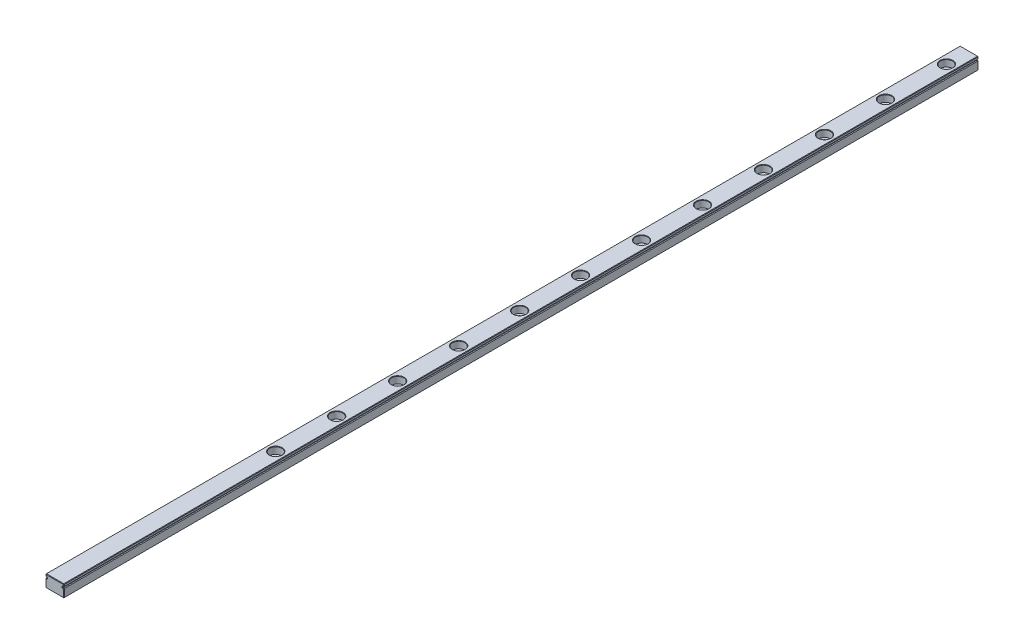
SolidWorks part; units mm, degrees
material "AISI 304"
ref_plane "Front Plane" through (0, 0, 0) normal (0, 0, 1) x (1, 0, 0)
ref_plane "Top Plane" through (0, 0, 0) normal (0, 1, 0) x (1, 0, 0)
ref_plane "Right Plane" through (0, 0, 0) normal (1, 0, 0) x (0, 0, -1)
sketch "Sketch1" plane through (0, 0, 0) normal (0, 0, 1) x (1, 0, 0)
  line L0 (0, 0) -> (0, 8) construction
  line L1 (0, 8) -> (12, 8)
  line L2 (0, 0) -> (12, 0)
  line L3 (0, 8) -> (0, 6.75)
  line L4 (0, 6.75) -> (0.5, 6.25) construction
  line L5 (0.5, 6.25) -> (1, 6.25)
  line L6 (0.5, 5.75) -> (0, 5.25) construction
  line L7 (0, 5.25) -> (0, 0)
  line L8 (1, 6.25) -> (1, 5.75)
  line L9 (1, 5.75) -> (0.5, 5.75)
  line L10 (0.5, 5.75) -> (0.75, 6) construction
  line L11 (0.75, 6) -> (0.5, 6.25) construction
  line L12 (0, 6.75) -> (0, 6.559)
  line L13 (0, 5.25) -> (0, 5.441)
  line L14 (6, 8) -> (6, 0) construction
  line L15 (11.25, 6) -> (11.5, 6.25) construction
  line L16 (11.5, 5.75) -> (11.25, 6) construction
  line L17 (11.5, 5.75) -> (12, 5.25) construction
  line L18 (12, 6.75) -> (11.5, 6.25) construction
  line L19 (12, 0) -> (12, 8) construction
  line L20 (12, 5.25) -> (12, 5.441)
  line L21 (12, 6.75) -> (12, 6.559)
  line L22 (11, 5.75) -> (11.5, 5.75)
  line L23 (11, 6.25) -> (11, 5.75)
  line L24 (12, 5.25) -> (12, 0)
  line L25 (11.5, 6.25) -> (11, 6.25)
  line L26 (12, 8) -> (12, 6.75)
  arc A0 (0, 5.441) -> (0.5, 5.75) centre (0, 6) ccw
  arc A1 (0.5, 6.25) -> (0, 6.559) centre (0, 6) ccw
  arc A2 (11.5, 6.25) -> (12, 6.559) centre (12, 6) cw
  arc A3 (12, 5.441) -> (11.5, 5.75) centre (12, 6) cw
  point P4 (1, 6)
  point P28 (11, 6)
  dimension "D1" = 8
  dimension "D2" = 6
  dimension "D3" = 0.5
  dimension "D4" = 45
  dimension "D5" = 2
  dimension "D6" = 1
extrude "Boss-Extrude1" add sketch "Sketch1" along normal blind 600
chamfer "Chamfer1" distance 0.3 angle 45 36 edges at (0, 0, 300) (12, 0, 300) (0, 8, 300) (12, 8, 300) (0.2939, 5.5245, 600) (0.75, 5.75, 600) (1, 6, 600) (0.75, 6.25, 600) (0.2939, 6.4755, 600) (0, 7.2795, 600) (6, 8, 600) (12, 7.2795, 600) (11.7061, 6.4755, 600) (11.25, 6.25, 600) (11, 6, 600) (11.25, 5.75, 600) (11.7061, 5.5245, 600) (12, 2.7205, 600) (6, 0, 600) (0, 2.7205, 600) (12, 2.7205, 0) (11.7061, 5.5245, 0) (11.25, 5.75, 0) (11, 6, 0) (11.25, 6.25, 0) (11.7061, 6.4755, 0) (12, 7.2795, 0) (6, 0, 0) (0, 2.7205, 0) (0.2939, 5.5245, 0) (0.75, 5.75, 0) (1, 6, 0) (0.75, 6.25, 0) (0.2939, 6.4755, 0) (0, 7.2795, 0) (6, 8, 0)
hole_wizard "CBORE for M5 Hex Head Bolt1" positions "3DSketch1" profile "Sketch3" counterbore size "M5" standard "ANSI Metric" end condition through all
sketch3d "3DSketch1"
  line L0 (6, 8, 0) -> (6, 8, 15) construction
  line L1 (11.7, 8, 0) -> (0.3, 8, 0) construction
  point P0 (6, 8, 15)
  dimension "D1" = 15
sketch "Sketch3" plane through (6, 8, 15) normal (1, 0, 0) x (0, 0, 1)
  line L0 (0, 0) -> (0, 8)
  line L1 (2.25, 7.75) -> (2.5, 8)
  line L2 (4, 4.5) -> (2.25, 4.5)
  line L3 (2.25, 4.5) -> (2.25, 7.75)
  line L5 (4, 4.5) -> (4, 0.25)
  line L6 (4, 0.25) -> (4.25, 0)
  line L7 (4.25, 0) -> (0, 0)
  line L8 (-4, 0.25) -> (-4.25, 0) construction
  line L11 (0, -6.35) -> (0, 107.95) construction
  line L12 (2.5, 8) -> (0, 8)
  line L13 (-2.25, 7.75) -> (-2.5, 8) construction
  dimension "Thru Hole Dia." = 4.5
  dimension "Thru Hole Depth" = 8
  dimension "C'Bore Dia." = 8
  dimension "C'Bore Depth" = 4.5
  dimension "Near C'Sink Dia." = 8.5
  dimension "Near C'Sink Angle" = 90
  dimension "Far C'Sink Dia." = 5
  dimension "Far C'Sink Angle" = 90
pattern_linear "LPattern1" count 12 spacing 40 along (0, 0, 1) of "CBORE for M5 Hex Head Bolt1"
sketch "Sketch4" plane through (0, 0, 600) normal (0, 0, 1) x (1, 0, 0)
  line L0 (6, 0.3) -> (6, 10.6503) construction
  line L1 (0.3, 0.3) -> (11.7, 0.3) construction
sketch "Sketch6" plane through (0, 0, 0) normal (0, 0, -1) x (-1, 0, 0)
  line L0 (-6, 0.3) -> (-6, 11.2574) construction
  line L1 (-11.7, 0.3) -> (-0.3, 0.3) construction
  line L2 (-6, 7.7) -> (-6, -3.7799) construction
  line L3 (-0.3, 7.7) -> (-11.7, 7.7) construction
sketch "Sketch8" plane through (0, 0, 0) normal (0, -1, 0) x (1, 0, 0)
  line L0 (6, -999.7) -> (6, 49000.3) construction
  line L1 (0.3, 0.3) -> (11.7, 0.3) construction
  point P5 (6, 0.3)
sketch "Sketch10" plane through (0, 0, 0) normal (0, 0, -1) x (-1, 0, 0)
  line L0 (-0.3, 4) -> (-11.7, 4) construction
  line L1 (-11.7, 0.3) -> (-0.3, 0.3) construction
  line L2 (-11.7, 5.1951) -> (-11.7, 0.3) construction
  line L3 (-6, 0.3) -> (-6, 7.7) construction
  line L4 (-0.3, 7.7) -> (-11.7, 7.7) construction
  point P12 (-6, 4)
